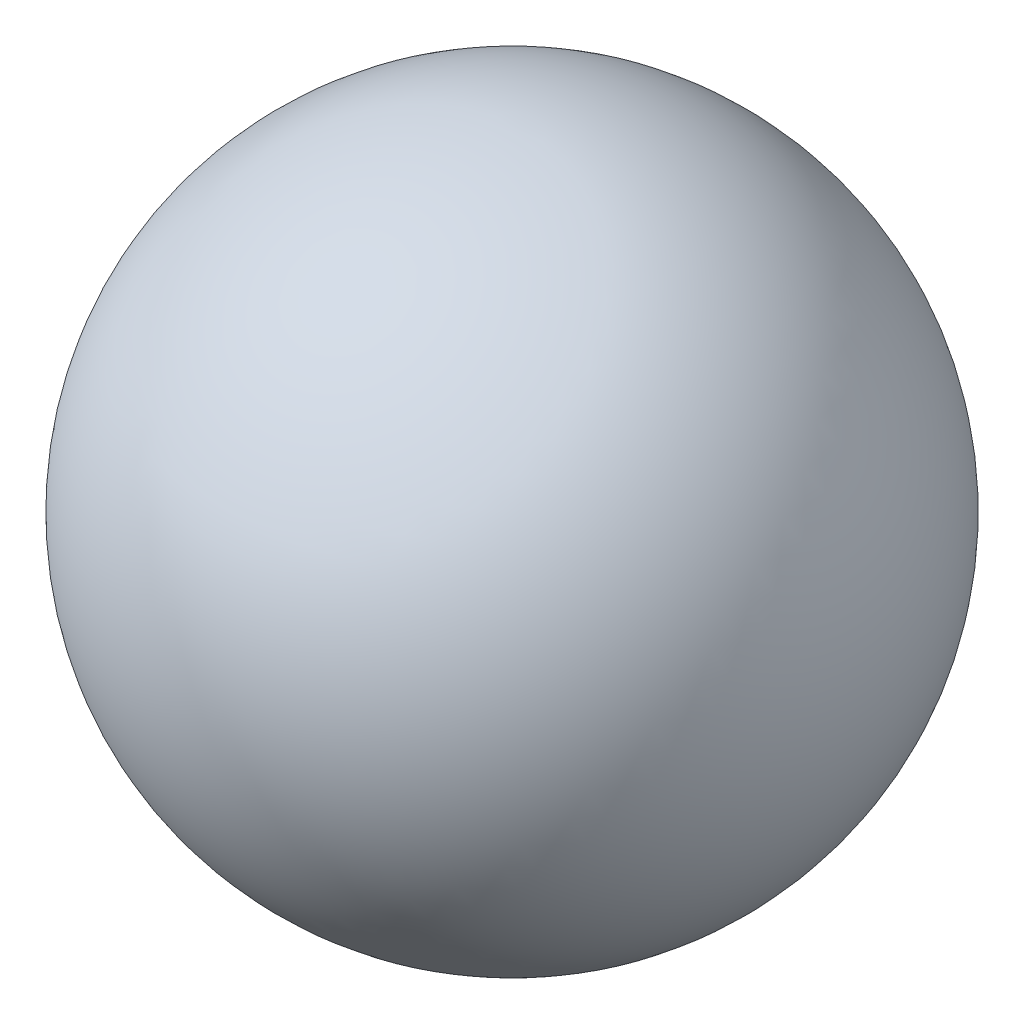
SolidWorks part; units mm, degrees
material "Plain Carbon Steel"
ref_plane "Front Plane" through (0, 0, 0) normal (0, 0, 1) x (1, 0, 0)
ref_plane "Top Plane" through (0, 0, 0) normal (0, 1, 0) x (1, 0, 0)
ref_plane "Right Plane" through (0, 0, 0) normal (1, 0, 0) x (0, 0, -1)
sketch "Sketch3" plane through (0, 0, 0) normal (0, 0, 1) x (1, 0, 0)
  line L0 (0, 3.5) -> (0, -3.5)
  arc A0 (0, 3.5) -> (0, -3.5) centre (0, 0) ccw
  dimension "D1" = 7
revolve "Revolve3" add sketch "Sketch3" angle 360 about L0
